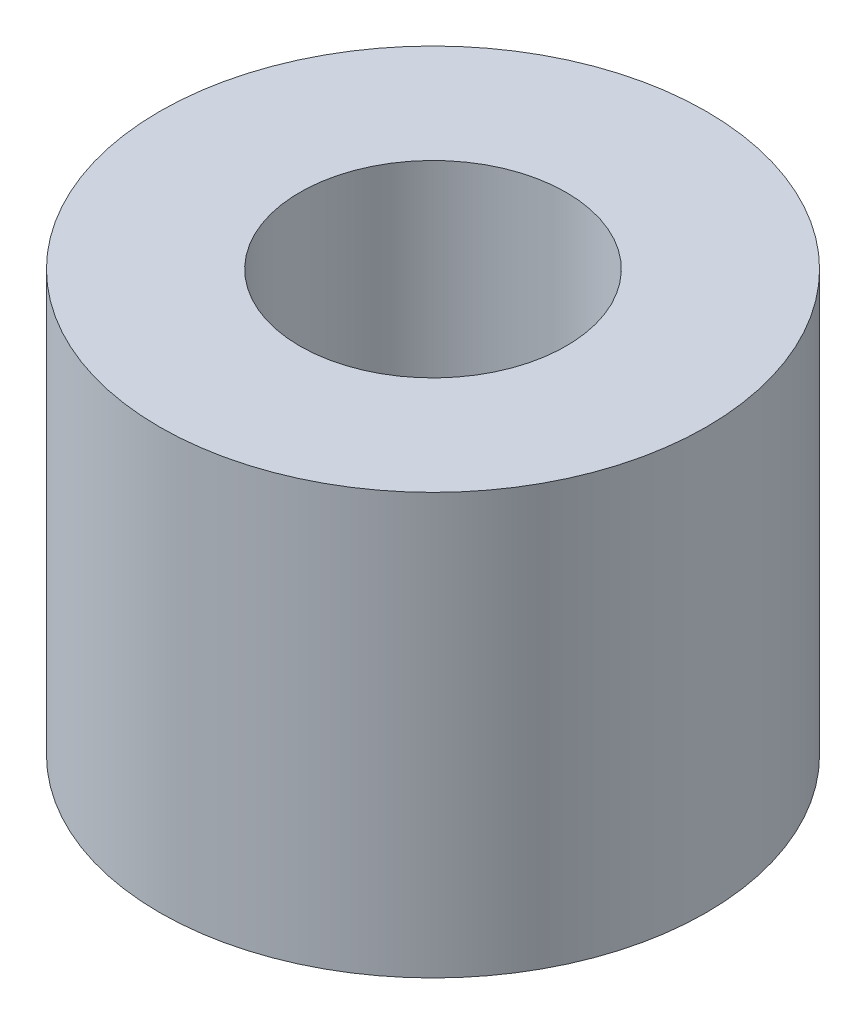
SolidWorks part; units mm, degrees
material "AISI 304"
ref_plane "Alzado" through (0, 0, 0) normal (0, 0, 1) x (1, 0, 0)
ref_plane "Planta" through (0, 0, 0) normal (0, 1, 0) x (1, 0, 0)
ref_plane "Vista lateral" through (0, 0, 0) normal (1, 0, 0) x (0, 0, -1)
sketch "Sketch1" plane through (0, 0, 0) normal (0, 0, 1) x (1, 0, 0)
  line L0 (1.9, -3) -> (3.9, -3)
  line L1 (3.9, -3) -> (3.9, 3)
  line L2 (3.9, 3) -> (1.9, 3)
  line L3 (1.9, 3) -> (1.9, -3)
  line L4 (0, -7) -> (0, 7) construction
revolve "Ojal_guia" add sketch "Sketch1" angle 360 about L4
